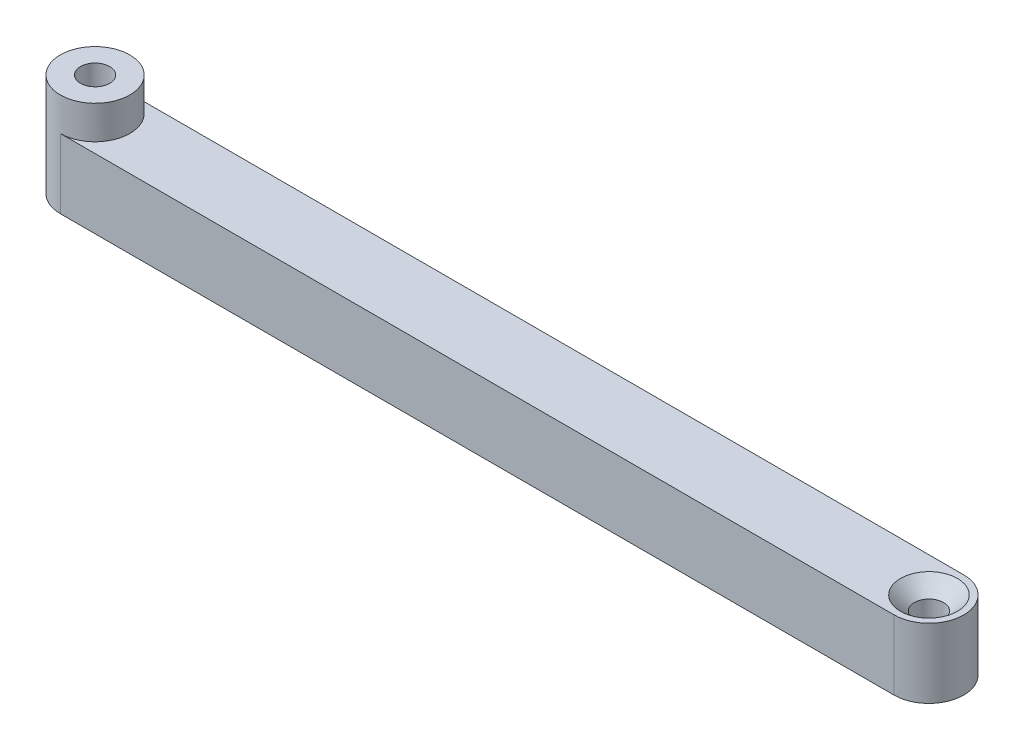
SolidWorks part; units mm, degrees
material "PET"
ref_plane "Front Plane" through (0, 0, 0) normal (0, 0, 1) x (1, 0, 0)
ref_plane "Top Plane" through (0, 0, 0) normal (0, 1, 0) x (1, 0, 0)
ref_plane "Right Plane" through (0, 0, 0) normal (1, 0, 0) x (0, 0, -1)
sketch "Sketch1" plane through (0, 0, 0) normal (0, 1, 0) x (1, 0, 0)
  line L0 (0, 0) -> (60, 0) construction
  line L1 (0, 2.5) -> (60, 2.5)
  line L2 (0, -2.5) -> (60, -2.5)
  arc A0 (0, 2.5) -> (0, -2.5) centre (0, 0) ccw
  arc A1 (60, -2.5) -> (60, 2.5) centre (60, 0) ccw
  circle A2 centre (0, 0) radius 1.05
  circle A3 centre (60, 0) radius 1.05
  point P3 (30, 0)
  dimension "D3" = 2.1
  dimension "D1" = 5
  dimension "D2" = 60
extrude "Boss-Extrude1" add sketch "Sketch1" along normal blind 5
chamfer "Chamfer1" distance 1 angle 45 1 edges at (60, 5, 1.05)
chamfer "Chamfer2" distance 1 angle 45 1 edges at (0, 0, 1.05)
sketch "Sketch2" plane through (0, 5, 0) normal (0, 1, 0) x (1, 0, 0)
  circle A0 centre (0, 0) radius 2.5
  circle A1 centre (0, 0) radius 1.05
extrude "Boss-Extrude2" add sketch "Sketch2" along normal blind 2.4
